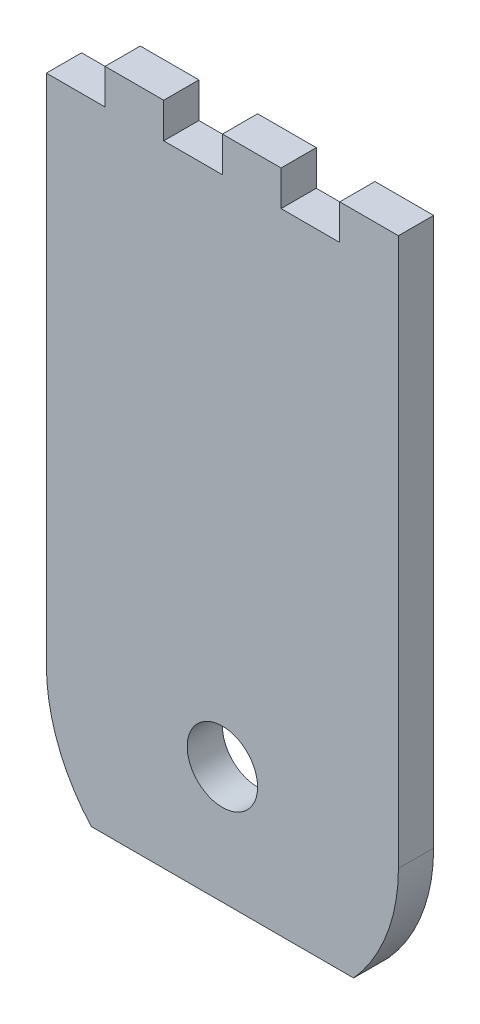
SolidWorks part; units mm, degrees
ref_plane "Alzado" through (0, 0, 0) normal (0, 0, 1) x (1, 0, 0)
ref_plane "Planta" through (0, 0, 0) normal (0, 1, 0) x (1, 0, 0)
ref_plane "Vista lateral" through (0, 0, 0) normal (1, 0, 0) x (0, 0, -1)
sketch "Croquis1" plane through (0, 0, 0) normal (0, 0, 1) x (1, 0, 0)
  line L0 (0, 28.345) -> (0, -18.345) construction
  line L1 (-15, -28.345) -> (15, -28.345)
  line L2 (-15, -28.345) -> (-15, 25.345)
  line L3 (-10, 28.345) -> (-5, 28.345)
  line L4 (15, -28.345) -> (15, 28.345)
  line L5 (-15, -28.345) -> (15, 28.345) construction
  line L6 (-15, 28.345) -> (15, -28.345) construction
  line L7 (-15, 25.345) -> (-10, 25.345)
  line L8 (-10, 25.345) -> (-10, 28.345)
  line L10 (-5, 28.345) -> (-5, 25.345)
  line L11 (-5, 25.345) -> (0, 25.345)
  line L12 (0, 25.345) -> (0, 28.345)
  line L14 (5, 28.345) -> (5, 25.345)
  line L15 (5, 25.345) -> (10, 25.345)
  line L16 (10, 25.345) -> (10, 28.345)
  line L17 (0, 28.345) -> (5, 28.345)
  line L18 (10, 28.345) -> (15, 28.345)
  line L19 (-15, -28.345) -> (-15, 28.345) construction
  line L20 (-15, 28.345) -> (15, 28.345) construction
  circle A0 centre (0, -18.345) radius 3
  point P0 (0, 0)
  dimension "D2" = 56.69
  dimension "D3" = 6
  dimension "D1" = 46.69
  dimension "D4" = 30
  dimension "D5" = 5
  dimension "D6" = 3
  dimension "D7" = 5
  dimension "D8" = 5
  dimension "D9" = 5
extrude "Saliente-Extruir1" add sketch "Croquis1" along normal blind 3
sketch "Croquis2" plane through (0, 0, 0) normal (0, 0, -1) x (-1, 0, 0)
  line L0 (-15, -18.345) -> (-21.1868, -18.345)
  line L1 (-21.1868, -18.345) -> (-21.1868, -37.1481)
  line L2 (-21.1868, -37.1481) -> (21.189, -37.1481)
  line L3 (21.189, -37.1481) -> (21.189, -18.345)
  line L4 (21.189, -18.345) -> (15, -18.345)
  arc A0 (-15, -18.345) -> (15, -18.345) centre (0, -18.345) ccw
  point P5 (-21.1868, -27.7465)
  dimension "D1" = 30
  dimension "D2" = 18.8031
  dimension "D3" = 42.3757
  dimension "D4" = 6.1868
extrude "Cortar-Extruir1" cut sketch "Croquis2" against normal blind 3
